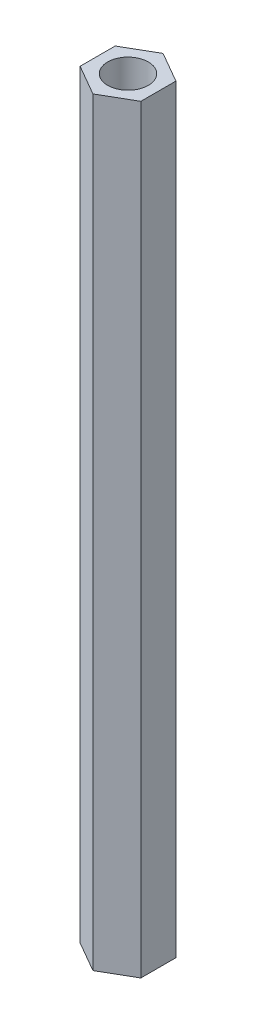
SolidWorks part; units mm, degrees
ref_plane "Front Plane" through (0, 0, 0) normal (0, 0, 1) x (1, 0, 0)
ref_plane "Top Plane" through (0, 0, 0) normal (0, 1, 0) x (1, 0, 0)
ref_plane "Right Plane" through (0, 0, 0) normal (1, 0, 0) x (0, 0, -1)
sketch "Sketch1" plane through (0, 0, 0) normal (0, 1, 0) x (1, 0, 0)
  line L1 (0, -2.0531) -> (1.778, -1.0265)
  line L2 (1.778, -1.0265) -> (1.778, 1.0265)
  line L3 (1.778, 1.0265) -> (0, 2.0531)
  line L4 (0, 2.0531) -> (-1.778, 1.0265)
  line L5 (-1.778, 1.0265) -> (-1.778, -1.0265)
  line L6 (-1.778, -1.0265) -> (0, -2.0531)
  circle A0 centre (0, 0) radius 1.778 construction
  circle A1 centre (0, 0) radius 1.1906
  dimension "D1" = 2.3813
  dimension "D2" = 1.778
extrude "Boss-Extrude1" add sketch "Sketch1" along normal blind 44.45
